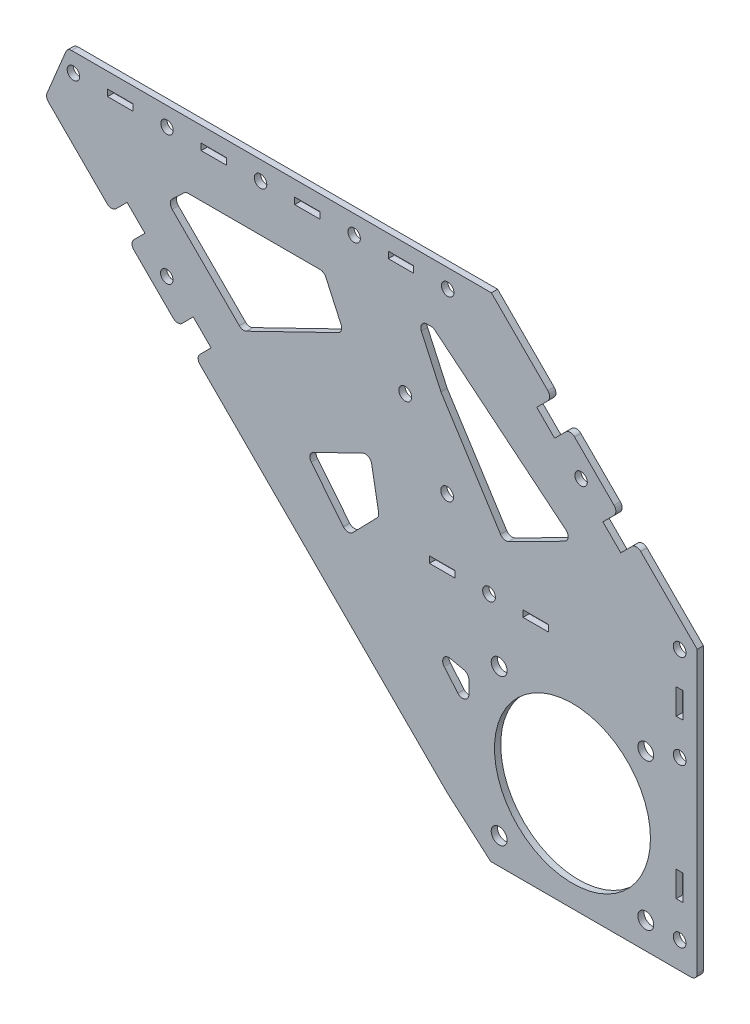
SolidWorks part; units mm, degrees
ref_plane "前视基准面" through (0, 0, 0) normal (0, 0, 1) x (1, 0, 0)
ref_plane "上视基准面" through (0, 0, 0) normal (0, 1, 0) x (1, 0, 0)
ref_plane "右视基准面" through (0, 0, 0) normal (1, 0, 0) x (0, 0, -1)
sketch "草图1" plane through (0, 0, 0) normal (0, 0, 1) x (1, 0, 0)
  line L261 (47.0274, 35.0547) -> (47.0274, 15.0547) construction
  line L315 (7.0274, -4.999) -> (20.8108, -16.957)
  line L316 (-52.9726, 135.0547) -> (-52.9726, 126.7057) construction
  line L332 (-112.9726, 135.0547) -> (-97.9726, 135.0547) construction
  line L334 (-42.0226, 136.1047) -> (-33.9226, 136.1047)
  line L335 (-42.0226, 136.1047) -> (-42.0226, 134.0047)
  line L336 (-42.0226, 134.0047) -> (-33.9226, 134.0047)
  line L337 (-33.9226, 136.1047) -> (-33.9226, 134.0047)
  line L338 (-42.0226, 136.1047) -> (-33.9226, 134.0047) construction
  line L339 (-42.0226, 134.0047) -> (-33.9226, 136.1047) construction
  line L389 (-114.8842, 141.0547) -> (21.0274, 141.0547)
  line L390 (-22.9726, 135.0547) -> (-22.9726, 144.5851) construction
  line L395 (-37.9726, 135.0547) -> (-7.9726, 135.0547) construction
  line L418 (87.0274, 75.0547) -> (21.0274, 141.0547) construction
  line L419 (-3.9226, 134.0047) -> (-12.0226, 136.1047) construction
  line L420 (-3.9226, 136.1047) -> (-12.0226, 134.0047) construction
  line L421 (7.0274, 135.0547) -> (-7.9726, 135.0547) construction
  line L422 (-12.0226, 136.1047) -> (-12.0226, 134.0047)
  line L423 (-3.9226, 134.0047) -> (-12.0226, 134.0047)
  line L424 (-3.9226, 136.1047) -> (-3.9226, 134.0047)
  line L443 (-3.9226, 136.1047) -> (-12.0226, 136.1047)
  line L444 (-102.0226, 136.1047) -> (-93.9226, 134.0047) construction
  line L445 (-102.0226, 134.0047) -> (-93.9226, 136.1047) construction
  line L446 (7.0274, -4.999) -> (-139.0436, 141.0882) construction
  line L447 (-67.9726, 135.0547) -> (-97.9726, 135.0547) construction
  line L448 (-104.2577, 114.7679) -> (-83.0445, 93.5547) construction
  line L449 (-63.9226, 134.0047) -> (-72.0226, 136.1047) construction
  line L483 (-63.9226, 136.1047) -> (-72.0226, 134.0047) construction
  line L515 (47.0274, 35.0547) -> (47.0274, 135.0547) construction
  line L516 (47.0274, 135.0547) -> (-52.9726, 135.0547) construction
  line L517 (-102.0226, 136.1047) -> (-93.9226, 136.1047)
  line L518 (-102.0226, 136.1047) -> (-102.0226, 134.0047)
  line L519 (-102.0226, 134.0047) -> (-93.9226, 134.0047)
  line L520 (-93.9226, 136.1047) -> (-93.9226, 134.0047)
  line L521 (-72.0226, 136.1047) -> (-72.0226, 134.0047)
  line L522 (-63.9226, 134.0047) -> (-72.0226, 134.0047)
  line L523 (-63.9226, 136.1047) -> (-63.9226, 134.0047)
  line L524 (-63.9226, 136.1047) -> (-72.0226, 136.1047)
  line L556 (21.4033, 132.1936) -> (81.3921, 72.2048) construction
  line L557 (54.0274, 108.0547) -> (35.0674, 89.0947) construction
  line L558 (42.7844, 112.2974) -> (35.5719, 116.54) construction
  line L559 (56.7851, 95.3268) -> (62.5127, 89.5993)
  line L576 (56.7851, 95.3268) -> (58.2701, 96.8117)
  line L577 (58.2701, 96.8117) -> (63.9976, 91.0842) construction
  line L578 (62.5127, 89.5993) -> (63.9976, 91.0842)
  line L579 (56.7851, 95.3268) -> (63.9976, 91.0842) construction
  line L580 (58.2701, 96.8117) -> (62.5127, 89.5993) construction
  line L581 (41.2995, 110.8124) -> (37.0569, 118.0249) construction
  line L582 (35.5719, 116.54) -> (37.0569, 118.0249)
  line L583 (42.7844, 112.2974) -> (37.0569, 118.0249) construction
  line L584 (41.2995, 110.8124) -> (42.7844, 112.2974)
  line L585 (41.2995, 110.8124) -> (35.5719, 116.54)
  line L586 (60.3914, 93.2055) -> (59.6489, 92.463) construction
  line L587 (39.1782, 114.4187) -> (38.4357, 113.6762) construction
  line L589 (20.2758, 57.0547) -> (5.2758, 57.0547) construction
  line L605 (-26.0184, 28.0504) -> (-21.7793, 32.2895) construction
  line L607 (-83.0445, 93.5547) -> (-87.2854, 89.3138) construction
  line L621 (-83.0445, 93.5547) -> (-61.8313, 72.3415) construction
  line L623 (73.2276, -16.9644) -> (87.0274, -16.9644)
  line L624 (23.5274, -8.4453) -> (70.5274, -8.4453) construction
  line L631 (-97.2574, 106.2827) -> (-91.5298, 100.5551) construction
  line L632 (-82.9726, 135.0547) -> (-82.9726, 64.2144) construction
  line L633 (-97.2574, 106.2827) -> (-95.7724, 107.7676)
  line L638 (-22.9726, 135.0547) -> (-22.9726, 124.9547) construction
  line L639 (87.0274, -16.9644) -> (87.0274, 75.0547)
  line L640 (20.2758, 57.0547) -> (20.2758, 57.6954) construction
  line L641 (9.3758, 56.0047) -> (1.1758, 56.0047)
  line L642 (9.3758, 56.0047) -> (9.3758, 58.1047)
  line L643 (9.3758, 58.1047) -> (1.1758, 58.1047)
  line L644 (1.1758, 56.0047) -> (1.1758, 58.1047)
  line L645 (9.3758, 56.0047) -> (1.1758, 58.1047) construction
  line L646 (9.3758, 58.1047) -> (1.1758, 56.0047) construction
  line L647 (31.1758, 58.1047) -> (39.3758, 56.0047) construction
  line L648 (31.1758, 56.0047) -> (39.3758, 58.1047) construction
  line L649 (39.3758, 56.0047) -> (39.3758, 58.1047)
  line L650 (31.1758, 58.1047) -> (39.3758, 58.1047)
  line L651 (31.1758, 56.0047) -> (31.1758, 58.1047)
  line L652 (31.1758, 56.0047) -> (39.3758, 56.0047)
  line L653 (-6.5853, 99.2267) -> (-61.8313, 72.3415) construction
  line L654 (-104.2577, 114.7679) -> (-82.9726, 135.0547) construction
  line L655 (-82.9726, 135.0547) -> (-22.9726, 135.0547) construction
  line L656 (-22.9726, 135.0547) -> (-6.5853, 99.2267) construction
  line L657 (-61.8313, 72.3415) -> (-104.2577, 114.7679) construction
  line L658 (-26.3178, 106.3059) -> (-58.7833, 90.5067)
  line L659 (-58.7833, 90.5067) -> (-82.7867, 114.5102)
  line L660 (-82.7867, 114.5102) -> (-76.9693, 120.0547)
  line L661 (-76.9693, 120.0547) -> (-32.6063, 120.0547)
  line L662 (-32.6063, 120.0547) -> (-26.3178, 106.3059)
  line L663 (70.998, 82.5989) -> (20.2758, 57.0547) construction
  line L664 (70.998, 82.5989) -> (7.0274, 135.0547) construction
  line L665 (7.0274, 135.0547) -> (-22.9726, 135.0547) construction
  line L667 (47.2997, 85.2197) -> (24.9262, 73.9522)
  line L668 (4.8626, 105.452) -> (24.9262, 73.9522)
  line L669 (-2.7313, 122.0547) -> (4.8626, 105.452)
  line L670 (2.3789, 122.0547) -> (-2.7313, 122.0547)
  line L671 (47.2997, 85.2197) -> (2.3789, 122.0547)
  line L672 (1.1758, 56.0047) -> (-6.5853, 99.2267) construction
  line L673 (-61.8313, 72.3415) -> (-26.0184, 28.0504) construction
  line L674 (-26.0184, 28.0504) -> (1.1758, 56.0047) construction
  line L675 (-14.9502, 60.9397) -> (-17.8458, 77.065)
  line L676 (-17.8458, 77.065) -> (-38.3086, 67.1069)
  line L677 (-38.3086, 67.1069) -> (-24.9829, 50.6265)
  line L678 (-24.9829, 50.6265) -> (-14.9502, 60.9397)
  line L679 (23.8026, -6.8752) -> (23.8026, 39.5844) construction
  line L680 (23.8026, 39.5844) -> (-24.9829, 50.6265) construction
  line L681 (-24.9829, 50.6265) -> (23.8026, -6.8752) construction
  line L682 (2.0144, 34.263) -> (13.8026, 20.3686)
  line L683 (13.8026, 20.3686) -> (13.8026, 31.5948)
  line L684 (13.8026, 31.5948) -> (2.0144, 34.263)
  line L685 (23.5274, -8.4453) -> (23.5274, 38.5547) construction
  line L686 (23.5274, 38.5547) -> (70.5274, 38.5547) construction
  line L687 (70.5274, -8.4453) -> (70.5274, 38.5547) construction
  line L688 (23.5274, -8.4453) -> (70.5274, 38.5547) construction
  line L689 (23.5274, 38.5547) -> (70.5274, -8.4453) construction
  line L690 (-91.5298, 100.5551) -> (-90.0449, 102.04)
  line L691 (-95.7724, 107.7676) -> (-90.0449, 102.04)
  line L692 (-97.2574, 106.2827) -> (-90.0449, 102.04) construction
  line L693 (-91.5298, 100.5551) -> (-95.7724, 107.7676) construction
  line L694 (-76.0442, 85.0695) -> (-68.8317, 80.8268) construction
  line L695 (-70.3166, 79.3419) -> (-74.5592, 86.5544) construction
  line L696 (-68.8317, 80.8268) -> (-74.5592, 86.5544)
  line L697 (-76.0442, 85.0695) -> (-74.5592, 86.5544)
  line L698 (-70.3166, 79.3419) -> (-68.8317, 80.8268)
  line L699 (-70.3166, 79.3419) -> (-76.0442, 85.0695) construction
  line L700 (-70.3166, 79.3419) -> (-73.815, 75.8434)
  line L701 (-76.0442, 85.0695) -> (-79.5426, 81.571)
  line L702 (-91.5298, 100.5551) -> (-95.0283, 97.0566)
  line L703 (-97.2574, 106.2827) -> (-100.7558, 102.7842)
  line L704 (-121.9553, 123.9837) -> (-100.7558, 102.7842)
  line L705 (-95.0283, 97.0566) -> (-87.2854, 89.3138)
  line L706 (-87.2854, 89.3138) -> (-79.5426, 81.571)
  line L707 (-73.815, 75.8434) -> (7.0274, -4.999)
  line L708 (37.0569, 118.0249) -> (40.557, 121.5251)
  line L709 (40.557, 121.5251) -> (21.0274, 141.0547)
  line L710 (42.7844, 112.2974) -> (46.2846, 115.7976)
  line L711 (46.2846, 115.7976) -> (54.0274, 108.0547)
  line L712 (54.0274, 108.0547) -> (61.7717, 100.3104)
  line L713 (61.7717, 100.3104) -> (58.2701, 96.8117)
  line L714 (63.9976, 91.0842) -> (67.4978, 94.5844)
  line L715 (67.4978, 94.5844) -> (87.0274, 75.0547)
  line L716 (20.8108, -16.957) -> (73.2276, -16.9644)
  line L717 (-6.5853, 99.2267) -> (20.2758, 57.0547) construction
  line L719 (81.3921, -8.4453) -> (81.3921, 72.2048) construction
  line L721 (-121.9553, 123.9837) -> (-114.8842, 141.0547)
  line L722 (80.2921, 53.1048) -> (82.4921, 53.1048)
  line L723 (80.2921, 53.1048) -> (80.2921, 61.3048)
  line L724 (80.2921, 61.3048) -> (82.4921, 61.3048)
  line L725 (82.4921, 53.1048) -> (82.4921, 61.3048)
  line L726 (80.2921, 53.1048) -> (82.4921, 61.3048) construction
  line L727 (80.2921, 61.3048) -> (82.4921, 53.1048) construction
  line L728 (80.2921, 2.4547) -> (82.4921, 2.4547)
  line L729 (80.2921, 2.4547) -> (80.2921, 10.6547)
  line L730 (80.2921, 10.6547) -> (82.4921, 10.6547)
  line L731 (82.4921, 2.4547) -> (82.4921, 10.6547)
  line L732 (80.2921, 2.4547) -> (82.4921, 10.6547) construction
  line L733 (80.2921, 10.6547) -> (82.4921, 2.4547) construction
  line L734 (-6.5853, 99.2267) -> (20.2758, 57.0547) construction
  circle A39 centre (-52.9726, 135.0547) radius 2
  circle A42 centre (47.0274, 15.0547) radius 25
  circle A49 centre (-22.9726, 135.0547) radius 2
  circle A69 centre (7.0274, 135.0547) radius 2
  circle A92 centre (-112.9726, 135.0547) radius 2
  circle A93 centre (-82.9726, 135.0547) radius 2
  circle A98 centre (49.7848, 103.8121) radius 2
  arc A115 (-114.8842, 141.0547) -> (-121.9553, 123.9837) centre (-114.8842, 131.0547) ccw construction
  circle A116 centre (-83.0445, 93.5547) radius 2
  circle A121 centre (20.2758, 57.0547) radius 2.05
  circle A122 centre (-6.5853, 99.2267) radius 2.05
  circle A123 centre (70.5274, -8.4453) radius 2.55
  circle A124 centre (23.5274, -8.4453) radius 2.55
  circle A125 centre (23.5274, 38.5547) radius 2.55
  circle A126 centre (70.5274, 38.5547) radius 2.55
  circle A127 centre (81.3921, 72.2048) radius 2.05
  circle A128 centre (81.3921, -8.4453) radius 2.05
  circle A129 centre (81.3921, 42.2048) radius 2.05
  circle A130 centre (6.8453, 78.1407) radius 2.05
  point P5 (210.9534, 218.4629)
  point P6 (288.6284, 218.4629)
  point P51 (-93.6511, 104.1613)
  point P54 (-105.4726, 135.0547)
  point P60 (60.3914, 93.2055)
  point P83 (-93.6511, 104.1613)
  point P98 (81.3921, 57.2048)
  point P115 (47.016, -39.6917)
  point P147 (-72.4379, 82.9481)
  point P152 (81.3921, 6.5547)
  dimension "D3" = 50
  dimension "D5" = 4
  dimension "D4" = 47
  dimension "D6" = 15
  dimension "D7" = 2.1
  dimension "D12" = 4
  dimension "D19" = 29.4043
  dimension "D20" = 2.2
  dimension "D22" = 4
  dimension "D8" = 30
  dimension "D28" = 8.2
  dimension "D26" = 10
  dimension "D17" = 10.1
  dimension "D29" = 42
  dimension "D30" = 15
  dimension "D31" = 80.6501
  dimension "D18" = 8.1
  dimension "D15" = 8.2
  dimension "D27" = 30
  dimension "D9" = 15
  dimension "D10" = 15
  dimension "D11" = 8.1
  dimension "D13" = 2.1
  dimension "D14" = 6
  dimension "D16" = 41.5
  dimension "D21" = 6
  dimension "D23" = 15
  dimension "D24" = 15
  dimension "D25" = 2.1
  dimension "D32" = 8.2
  dimension "D33" = 2.1
  dimension "D34" = 120
  dimension "D35" = 70
  dimension "D36" = 15
  dimension "D37" = 13
  dimension "D38" = 15
  dimension "D39" = 10
extrude "凸台-拉伸1" add sketch "草图1" along normal blind 2
fillet "圆角2" radius 2 27 edges at (-76.9693, 120.0547, 1) (-82.7867, 114.5102, 1) (-32.6063, 120.0547, 1) (-26.3178, 106.3059, 1) (-58.7833, 90.5067, 1) (-17.8458, 77.065, 1) (-14.9502, 60.9397, 1) (-24.9829, 50.6265, 1) (-38.3086, 67.1069, 1) (47.2997, 85.2197, 1) (24.9262, 73.9522, 1) (2.3789, 122.0547, 1) (-2.7313, 122.0547, 1) (13.8026, 31.5948, 1) (2.0144, 34.263, 1) (13.8026, 20.3686, 1) (87.0274, -16.9644, 1) (-100.7558, 102.7842, 1) (-95.0283, 97.0566, 1) (-79.5426, 81.571, 1) (-73.815, 75.8434, 1) (67.4978, 94.5844, 1) (61.7717, 100.3104, 1) (46.2846, 115.7976, 1) (40.557, 121.5251, 1) (-114.8842, 141.0547, 1) (-121.9553, 123.9837, 1)
